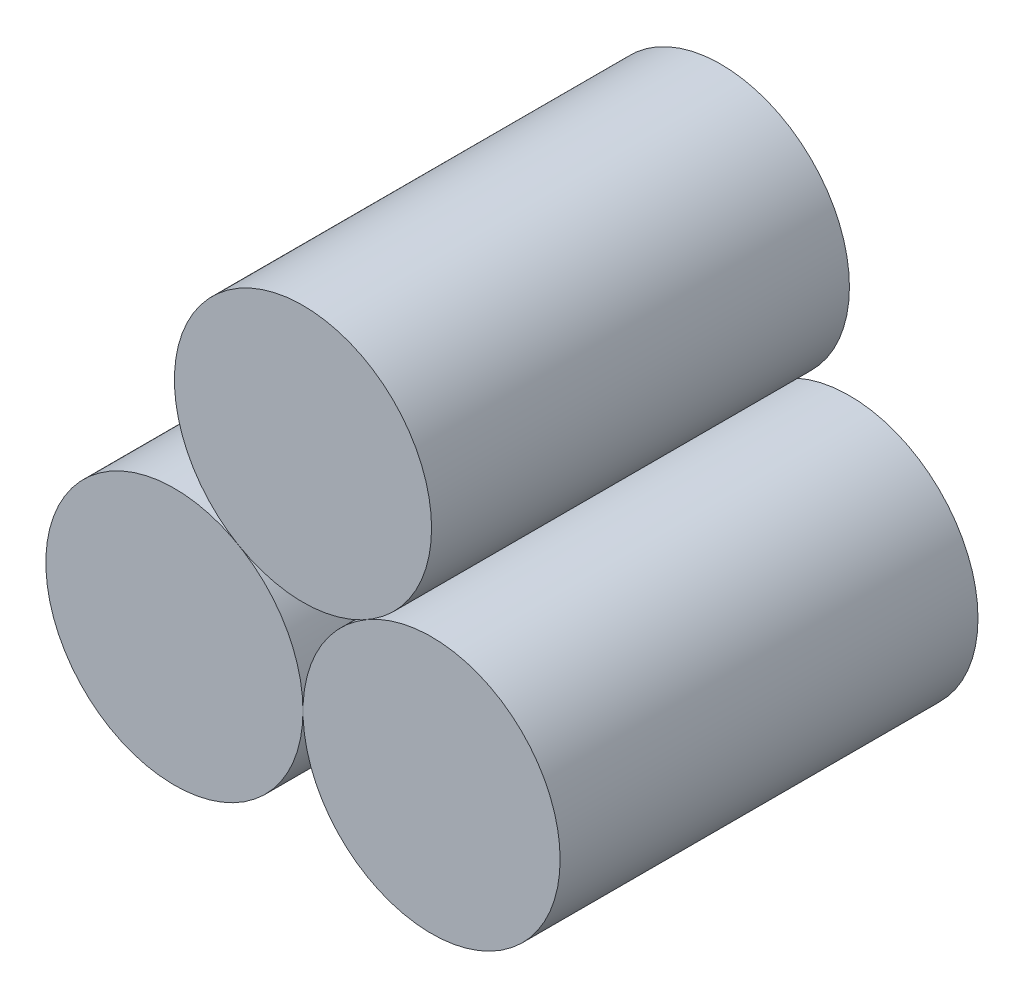
SolidWorks part; units mm, degrees
ref_plane "Спереди" through (0, 0, 0) normal (0, 0, 1) x (1, 0, 0)
ref_plane "Сверху" through (0, 0, 0) normal (0, 1, 0) x (1, 0, 0)
ref_plane "Справа" through (0, 0, 0) normal (1, 0, 0) x (0, 0, -1)
sketch "Эскиз1" plane through (0, 0, 0) normal (0, 0, 1) x (1, 0, 0)
  line L0 (-2.5891, 6.4845) -> (2, 3.8349) construction
  line L1 (-0.8391, 9.5155) -> (-4.3391, 3.4534) construction
  line L2 (2.5891, 6.4845) -> (-2, 3.8349) construction
  line L3 (4.3391, 3.4534) -> (0.8391, 9.5155) construction
  line L4 (0, 2) -> (0, 7.299) construction
  line L6 (-3.5, 2) -> (3.5, 2) construction
  circle A0 centre (0, 7.299) radius 2
  circle A1 centre (-2, 3.8349) radius 2
  circle A2 centre (2, 3.8349) radius 2
  dimension "D2" = 4
extrude "Бобышка-Вытянуть1" add sketch "Эскиз1" along normal blind 2.5 and the other way blind 4 contours A1 | A0 | A2
